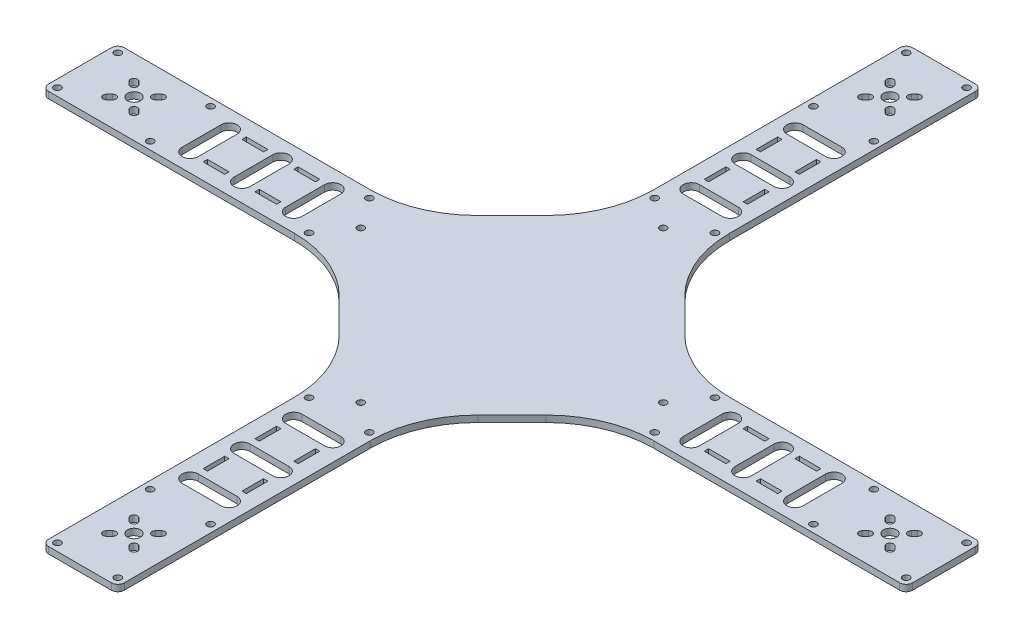
SolidWorks part; units mm, degrees
ref_plane "前视基准面" through (0, 0, 0) normal (0, 0, 1) x (1, 0, 0)
ref_plane "上视基准面" through (0, 0, 0) normal (0, 1, 0) x (1, 0, 0)
ref_plane "右视基准面" through (0, 0, 0) normal (1, 0, 0) x (0, 0, -1)
other "Configuration Table"
sketch "基本底盘" plane through (0, 0, 0) normal (0, 1, 0) x (1, 0, 0)
  line L0 (0, 0) -> (0, -350) construction
  line L1 (4.9497, -4.9497) -> (6.364, -6.364) construction
  line L4 (6.0811, -3.8184) -> (7.4953, -5.2326)
  line L5 (3.8184, -6.0811) -> (5.2326, -7.4953)
  line L6 (-17.5, 25) -> (17.5, 25)
  line L9 (-4.9497, -4.9497) -> (-6.364, -6.364) construction
  line L10 (-3.8184, -6.0811) -> (-5.2326, -7.4953)
  line L11 (-6.0811, -3.8184) -> (-7.4953, -5.2326)
  line L12 (-17.5, 25) -> (-17.5, -25)
  line L15 (-4.9497, 4.9497) -> (-6.364, 6.364) construction
  line L16 (-6.0811, 3.8184) -> (-7.4953, 5.2326)
  line L17 (-3.8184, 6.0811) -> (-5.2326, 7.4953)
  line L18 (17.5, 25) -> (17.5, -25)
  line L21 (4.9497, 4.9497) -> (6.364, 6.364) construction
  line L22 (3.8184, 6.0811) -> (5.2326, 7.4953)
  line L23 (6.0811, 3.8184) -> (7.4953, 5.2326)
  line L24 (0, -25) -> (0, -35)
  line L25 (-9, -35) -> (9, -35) construction
  line L26 (-9, -59) -> (9, -59) construction
  line L27 (-17.5, -25) -> (17.5, -25) construction
  line L28 (-17.5, 25) -> (17.5, -25) construction
  line L29 (17.5, 25) -> (-17.5, -25) construction
  line L30 (-17.5, 25) -> (-13.9645, 21.4645)
  line L31 (-17.5, 0) -> (17.5, 0) construction
  line L32 (-80, -175) -> (80, -175)
  line L33 (0, -95) -> (0, -255)
  line L34 (-32.1447, -127.1447) -> (-47.8553, -142.8553)
  line L35 (32.1447, -222.8553) -> (47.8553, -207.1447)
  line L36 (47.8553, -142.8553) -> (32.1447, -127.1447)
  line L37 (-47.8553, -207.1447) -> (-32.1447, -222.8553)
  line L38 (-13.9645, -21.4645) -> (-13.9645, -95) construction
  line L39 (-17.5, -25) -> (-17.5, -91.7893)
  line L40 (17.5, -25) -> (17.5, -91.7893)
  line L41 (0, -95) -> (0, -105)
  line L42 (-9, -31.25) -> (9, -31.25)
  line L43 (-9, -38.75) -> (9, -38.75)
  line L44 (-9, -55.25) -> (9, -55.25)
  line L45 (-9, -62.75) -> (9, -62.75)
  line L46 (-9, -83) -> (9, -83) construction
  line L47 (-9, -79.25) -> (9, -79.25)
  line L48 (-9, -86.75) -> (9, -86.75)
  line L49 (9, -38.75) -> (9, -55.25)
  line L50 (8, -42) -> (10, -42)
  line L51 (8, -42) -> (8, -52)
  line L52 (10, -42) -> (10, -52)
  line L53 (8, -52) -> (10, -52)
  line L54 (8, -42) -> (10, -52) construction
  line L55 (10, -42) -> (8, -52) construction
  line L56 (8, -66) -> (10, -76) construction
  line L57 (10, -66) -> (8, -76) construction
  line L58 (8, -66) -> (10, -66)
  line L59 (8, -66) -> (8, -76)
  line L60 (8, -76) -> (10, -76)
  line L61 (10, -66) -> (10, -76)
  line L62 (-8, -66) -> (-8, -76)
  line L63 (-8, -76) -> (-10, -76)
  line L64 (-10, -66) -> (-10, -76)
  line L65 (-8, -66) -> (-10, -66)
  line L66 (-8, -52) -> (-10, -52)
  line L67 (-8, -42) -> (-8, -52)
  line L68 (-8, -42) -> (-10, -42)
  line L69 (-10, -42) -> (-10, -52)
  line L70 (200, -157.5) -> (200, -192.5)
  line L71 (200, -157.5) -> (150, -157.5)
  line L72 (200, -192.5) -> (150, -192.5)
  line L73 (150, -175) -> (140, -175)
  line L74 (200, -157.5) -> (196.4645, -161.0355)
  line L75 (136.25, -184) -> (119.75, -184)
  line L76 (133, -183) -> (133, -185)
  line L77 (133, -183) -> (123, -183)
  line L78 (133, -185) -> (123, -185)
  line L79 (123, -183) -> (123, -185)
  line L80 (109, -183) -> (109, -185)
  line L81 (109, -183) -> (99, -183)
  line L82 (99, -183) -> (99, -185)
  line L83 (109, -185) -> (99, -185)
  line L84 (109, -167) -> (99, -167)
  line L85 (99, -167) -> (99, -165)
  line L86 (109, -165) -> (99, -165)
  line L87 (109, -167) -> (109, -165)
  line L88 (123, -167) -> (123, -165)
  line L89 (133, -167) -> (123, -167)
  line L90 (133, -167) -> (133, -165)
  line L91 (133, -165) -> (123, -165)
  line L92 (150, -157.5) -> (150, -192.5) construction
  line L93 (200, -157.5) -> (150, -192.5) construction
  line L94 (200, -192.5) -> (150, -157.5) construction
  line L95 (175, -157.5) -> (175, -192.5) construction
  line L96 (153.5355, -161.0355) -> (80, -161.0355) construction
  line L97 (133, -183) -> (123, -185) construction
  line L98 (133, -185) -> (123, -183) construction
  line L99 (109, -183) -> (99, -185) construction
  line L100 (109, -185) -> (99, -183) construction
  line L101 (150, -157.5) -> (83.2107, -157.5)
  line L102 (150, -192.5) -> (83.2107, -192.5)
  line L103 (170.0503, -179.9497) -> (168.636, -181.364) construction
  line L104 (171.1816, -181.0811) -> (169.7674, -182.4953)
  line L105 (168.9189, -178.8184) -> (167.5047, -180.2326)
  line L106 (170.0503, -170.0503) -> (168.636, -168.636) construction
  line L107 (168.9189, -171.1816) -> (167.5047, -169.7674)
  line L108 (171.1816, -168.9189) -> (169.7674, -167.5047)
  line L109 (179.9497, -170.0503) -> (181.364, -168.636) construction
  line L110 (178.8184, -168.9189) -> (180.2326, -167.5047)
  line L111 (181.0811, -171.1816) -> (182.4953, -169.7674)
  line L112 (179.9497, -179.9497) -> (181.364, -181.364) construction
  line L113 (181.0811, -178.8184) -> (182.4953, -180.2326)
  line L114 (178.8184, -181.0811) -> (180.2326, -182.4953)
  line L115 (140, -166) -> (140, -184) construction
  line L116 (143.75, -166) -> (143.75, -184)
  line L117 (136.25, -166) -> (136.25, -184)
  line L118 (116, -166) -> (116, -184) construction
  line L119 (119.75, -166) -> (119.75, -184)
  line L120 (112.25, -166) -> (112.25, -184)
  line L121 (92, -166) -> (92, -184) construction
  line L122 (95.75, -166) -> (95.75, -184)
  line L123 (88.25, -166) -> (88.25, -184)
  line L124 (17.5, -375) -> (-17.5, -375)
  line L125 (17.5, -375) -> (17.5, -325)
  line L126 (-17.5, -375) -> (-17.5, -325)
  line L127 (0, -325) -> (0, -315)
  line L128 (17.5, -375) -> (13.9645, -371.4645)
  line L129 (-9, -311.25) -> (-9, -294.75)
  line L130 (-8, -308) -> (-10, -308)
  line L131 (-8, -308) -> (-8, -298)
  line L132 (-10, -308) -> (-10, -298)
  line L133 (-8, -298) -> (-10, -298)
  line L134 (-8, -284) -> (-10, -284)
  line L135 (-8, -284) -> (-8, -274)
  line L136 (-8, -274) -> (-10, -274)
  line L137 (-10, -284) -> (-10, -274)
  line L138 (8, -284) -> (8, -274)
  line L139 (8, -274) -> (10, -274)
  line L140 (10, -284) -> (10, -274)
  line L141 (8, -284) -> (10, -284)
  line L142 (8, -298) -> (10, -298)
  line L143 (8, -308) -> (8, -298)
  line L144 (8, -308) -> (10, -308)
  line L145 (10, -308) -> (10, -298)
  line L146 (17.5, -325) -> (-17.5, -325) construction
  line L147 (17.5, -375) -> (-17.5, -325) construction
  line L148 (-17.5, -375) -> (17.5, -325) construction
  line L149 (17.5, -350) -> (-17.5, -350) construction
  line L150 (13.9645, -328.5355) -> (13.9645, -255) construction
  line L151 (-8, -308) -> (-10, -298) construction
  line L152 (-10, -308) -> (-8, -298) construction
  line L153 (-8, -284) -> (-10, -274) construction
  line L154 (-10, -284) -> (-8, -274) construction
  line L155 (17.5, -325) -> (17.5, -258.2107)
  line L156 (-17.5, -325) -> (-17.5, -258.2107)
  line L157 (-4.9497, -345.0503) -> (-6.364, -343.636) construction
  line L158 (-6.0811, -346.1816) -> (-7.4953, -344.7674)
  line L159 (-3.8184, -343.9189) -> (-5.2326, -342.5047)
  line L160 (4.9497, -345.0503) -> (6.364, -343.636) construction
  line L161 (3.8184, -343.9189) -> (5.2326, -342.5047)
  line L162 (6.0811, -346.1816) -> (7.4953, -344.7674)
  line L163 (4.9497, -354.9497) -> (6.364, -356.364) construction
  line L164 (6.0811, -353.8184) -> (7.4953, -355.2326)
  line L165 (3.8184, -356.0811) -> (5.2326, -357.4953)
  line L166 (-4.9497, -354.9497) -> (-6.364, -356.364) construction
  line L167 (-3.8184, -356.0811) -> (-5.2326, -357.4953)
  line L168 (-6.0811, -353.8184) -> (-7.4953, -355.2326)
  line L169 (9, -315) -> (-9, -315) construction
  line L170 (9, -318.75) -> (-9, -318.75)
  line L171 (9, -311.25) -> (-9, -311.25)
  line L172 (9, -291) -> (-9, -291) construction
  line L173 (9, -294.75) -> (-9, -294.75)
  line L174 (9, -287.25) -> (-9, -287.25)
  line L175 (9, -267) -> (-9, -267) construction
  line L176 (9, -270.75) -> (-9, -270.75)
  line L177 (9, -263.25) -> (-9, -263.25)
  line L178 (-200, -192.5) -> (-200, -157.5)
  line L179 (-200, -192.5) -> (-150, -192.5)
  line L180 (-200, -157.5) -> (-150, -157.5)
  line L181 (-150, -175) -> (-140, -175)
  line L182 (-200, -192.5) -> (-196.4645, -188.9645)
  line L183 (-136.25, -166) -> (-119.75, -166)
  line L184 (-133, -167) -> (-133, -165)
  line L185 (-133, -167) -> (-123, -167)
  line L186 (-133, -165) -> (-123, -165)
  line L187 (-123, -167) -> (-123, -165)
  line L188 (-109, -167) -> (-109, -165)
  line L189 (-109, -167) -> (-99, -167)
  line L190 (-99, -167) -> (-99, -165)
  line L191 (-109, -165) -> (-99, -165)
  line L192 (-109, -183) -> (-99, -183)
  line L193 (-99, -183) -> (-99, -185)
  line L194 (-109, -185) -> (-99, -185)
  line L195 (-109, -183) -> (-109, -185)
  line L196 (-123, -183) -> (-123, -185)
  line L197 (-133, -183) -> (-123, -183)
  line L198 (-133, -183) -> (-133, -185)
  line L199 (-133, -185) -> (-123, -185)
  line L200 (-150, -192.5) -> (-150, -157.5) construction
  line L201 (-200, -192.5) -> (-150, -157.5) construction
  line L202 (-200, -157.5) -> (-150, -192.5) construction
  line L203 (-175, -192.5) -> (-175, -157.5) construction
  line L204 (-153.5355, -188.9645) -> (-80, -188.9645) construction
  line L205 (-133, -167) -> (-123, -165) construction
  line L206 (-133, -165) -> (-123, -167) construction
  line L207 (-109, -167) -> (-99, -165) construction
  line L208 (-109, -165) -> (-99, -167) construction
  line L209 (-150, -192.5) -> (-83.2107, -192.5)
  line L210 (-150, -157.5) -> (-83.2107, -157.5)
  line L211 (-170.0503, -170.0503) -> (-168.636, -168.636) construction
  line L212 (-171.1816, -168.9189) -> (-169.7674, -167.5047)
  line L213 (-168.9189, -171.1816) -> (-167.5047, -169.7674)
  line L214 (-170.0503, -179.9497) -> (-168.636, -181.364) construction
  line L215 (-168.9189, -178.8184) -> (-167.5047, -180.2326)
  line L216 (-171.1816, -181.0811) -> (-169.7674, -182.4953)
  line L217 (-179.9497, -179.9497) -> (-181.364, -181.364) construction
  line L218 (-178.8184, -181.0811) -> (-180.2326, -182.4953)
  line L219 (-181.0811, -178.8184) -> (-182.4953, -180.2326)
  line L220 (-179.9497, -170.0503) -> (-181.364, -168.636) construction
  line L221 (-181.0811, -171.1816) -> (-182.4953, -169.7674)
  line L222 (-178.8184, -168.9189) -> (-180.2326, -167.5047)
  line L223 (-140, -184) -> (-140, -166) construction
  line L224 (-143.75, -184) -> (-143.75, -166)
  line L225 (-136.25, -184) -> (-136.25, -166)
  line L226 (-116, -184) -> (-116, -166) construction
  line L227 (-119.75, -184) -> (-119.75, -166)
  line L228 (-112.25, -184) -> (-112.25, -166)
  line L229 (-92, -184) -> (-92, -166) construction
  line L230 (-95.75, -184) -> (-95.75, -166)
  line L231 (-88.25, -184) -> (-88.25, -166)
  line L232 (0, -95) -> (-32.1447, -127.1447)
  line L233 (0, -95) -> (32.1447, -127.1447)
  line L234 (47.8553, -142.8553) -> (80, -175)
  line L235 (47.8553, -207.1447) -> (80, -175)
  line L236 (-80, -175) -> (-47.8553, -207.1447)
  line L237 (-80, -175) -> (-47.8553, -142.8553)
  line L238 (-32.1447, -222.8553) -> (0, -255)
  line L239 (0, -255) -> (32.1447, -222.8553)
  circle A0 centre (0, 0) radius 8 construction
  arc A3 (6.0811, -3.8184) -> (3.8184, -6.0811) centre (4.9497, -4.9497) ccw
  arc A4 (5.2326, -7.4953) -> (7.4953, -5.2326) centre (6.364, -6.364) ccw
  arc A7 (-3.8184, -6.0811) -> (-6.0811, -3.8184) centre (-4.9497, -4.9497) ccw
  arc A8 (-7.4953, -5.2326) -> (-5.2326, -7.4953) centre (-6.364, -6.364) ccw
  arc A11 (-6.0811, 3.8184) -> (-3.8184, 6.0811) centre (-4.9497, 4.9497) ccw
  arc A12 (-5.2326, 7.4953) -> (-7.4953, 5.2326) centre (-6.364, 6.364) ccw
  arc A15 (3.8184, 6.0811) -> (6.0811, 3.8184) centre (4.9497, 4.9497) ccw
  arc A16 (7.4953, 5.2326) -> (5.2326, 7.4953) centre (6.364, 6.364) ccw
  circle A17 centre (0, 0) radius 14 construction
  arc A18 (-9, -31.25) -> (-9, -38.75) centre (-9, -35) ccw
  arc A19 (9, -38.75) -> (9, -31.25) centre (9, -35) ccw
  circle A20 centre (0, 0) radius 3
  circle A21 centre (0, 0) radius 88.9 construction
  circle A22 centre (0, 0) radius 64.77 construction
  circle A23 centre (-13.9645, 21.4645) radius 1.6
  circle A24 centre (13.9645, 21.4645) radius 1.6
  circle A25 centre (13.9645, -21.4645) radius 1.6
  circle A26 centre (-13.9645, -21.4645) radius 1.6
  circle A27 centre (-13.9645, -95) radius 1.6
  circle A28 centre (13.9645, -95) radius 1.6
  circle A29 centre (0, -105) radius 1.6
  arc A30 (-9, -55.25) -> (-9, -62.75) centre (-9, -59) ccw
  arc A31 (9, -62.75) -> (9, -55.25) centre (9, -59) ccw
  arc A32 (-9, -79.25) -> (-9, -86.75) centre (-9, -83) ccw
  arc A33 (9, -86.75) -> (9, -79.25) centre (9, -83) ccw
  circle A34 centre (175, -175) radius 3
  circle A35 centre (196.4645, -161.0355) radius 1.6
  circle A36 centre (196.4645, -188.9645) radius 1.6
  circle A37 centre (153.5355, -188.9645) radius 1.6
  circle A38 centre (153.5355, -161.0355) radius 1.6
  circle A39 centre (80, -161.0355) radius 1.6
  circle A40 centre (80, -188.9645) radius 1.6
  circle A41 centre (175, -175) radius 8 construction
  circle A42 centre (175, -175) radius 14 construction
  circle A43 centre (175, -175) radius 88.9 construction
  circle A44 centre (175, -175) radius 64.77 construction
  circle A45 centre (70, -175) radius 1.6
  arc A46 (171.1816, -181.0811) -> (168.9189, -178.8184) centre (170.0503, -179.9497) ccw
  arc A47 (167.5047, -180.2326) -> (169.7674, -182.4953) centre (168.636, -181.364) ccw
  arc A48 (168.9189, -171.1816) -> (171.1816, -168.9189) centre (170.0503, -170.0503) ccw
  arc A49 (169.7674, -167.5047) -> (167.5047, -169.7674) centre (168.636, -168.636) ccw
  arc A50 (178.8184, -168.9189) -> (181.0811, -171.1816) centre (179.9497, -170.0503) ccw
  arc A51 (182.4953, -169.7674) -> (180.2326, -167.5047) centre (181.364, -168.636) ccw
  arc A52 (181.0811, -178.8184) -> (178.8184, -181.0811) centre (179.9497, -179.9497) ccw
  arc A53 (180.2326, -182.4953) -> (182.4953, -180.2326) centre (181.364, -181.364) ccw
  arc A54 (143.75, -166) -> (136.25, -166) centre (140, -166) ccw
  arc A55 (136.25, -184) -> (143.75, -184) centre (140, -184) ccw
  arc A56 (119.75, -166) -> (112.25, -166) centre (116, -166) ccw
  arc A57 (112.25, -184) -> (119.75, -184) centre (116, -184) ccw
  arc A58 (95.75, -166) -> (88.25, -166) centre (92, -166) ccw
  arc A59 (88.25, -184) -> (95.75, -184) centre (92, -184) ccw
  circle A60 centre (0, -350) radius 3
  circle A61 centre (13.9645, -371.4645) radius 1.6
  circle A62 centre (-13.9645, -371.4645) radius 1.6
  circle A63 centre (-13.9645, -328.5355) radius 1.6
  circle A64 centre (13.9645, -328.5355) radius 1.6
  circle A65 centre (13.9645, -255) radius 1.6
  circle A66 centre (-13.9645, -255) radius 1.6
  circle A67 centre (0, -350) radius 8 construction
  circle A68 centre (0, -350) radius 14 construction
  circle A69 centre (0, -350) radius 88.9 construction
  circle A70 centre (0, -350) radius 64.77 construction
  circle A71 centre (0, -245) radius 1.6
  arc A72 (-6.0811, -346.1816) -> (-3.8184, -343.9189) centre (-4.9497, -345.0503) ccw
  arc A73 (-5.2326, -342.5047) -> (-7.4953, -344.7674) centre (-6.364, -343.636) ccw
  arc A74 (3.8184, -343.9189) -> (6.0811, -346.1816) centre (4.9497, -345.0503) ccw
  arc A75 (7.4953, -344.7674) -> (5.2326, -342.5047) centre (6.364, -343.636) ccw
  arc A76 (6.0811, -353.8184) -> (3.8184, -356.0811) centre (4.9497, -354.9497) ccw
  arc A77 (5.2326, -357.4953) -> (7.4953, -355.2326) centre (6.364, -356.364) ccw
  arc A78 (-3.8184, -356.0811) -> (-6.0811, -353.8184) centre (-4.9497, -354.9497) ccw
  arc A79 (-7.4953, -355.2326) -> (-5.2326, -357.4953) centre (-6.364, -356.364) ccw
  arc A80 (9, -318.75) -> (9, -311.25) centre (9, -315) ccw
  arc A81 (-9, -311.25) -> (-9, -318.75) centre (-9, -315) ccw
  arc A82 (9, -294.75) -> (9, -287.25) centre (9, -291) ccw
  arc A83 (-9, -287.25) -> (-9, -294.75) centre (-9, -291) ccw
  arc A84 (9, -270.75) -> (9, -263.25) centre (9, -267) ccw
  arc A85 (-9, -263.25) -> (-9, -270.75) centre (-9, -267) ccw
  circle A86 centre (-175, -175) radius 3
  circle A87 centre (-196.4645, -188.9645) radius 1.6
  circle A88 centre (-196.4645, -161.0355) radius 1.6
  circle A89 centre (-153.5355, -161.0355) radius 1.6
  circle A90 centre (-153.5355, -188.9645) radius 1.6
  circle A91 centre (-80, -188.9645) radius 1.6
  circle A92 centre (-80, -161.0355) radius 1.6
  circle A93 centre (-175, -175) radius 8 construction
  circle A94 centre (-175, -175) radius 14 construction
  circle A95 centre (-175, -175) radius 88.9 construction
  circle A96 centre (-175, -175) radius 64.77 construction
  circle A97 centre (-70, -175) radius 1.6
  arc A98 (-171.1816, -168.9189) -> (-168.9189, -171.1816) centre (-170.0503, -170.0503) ccw
  arc A99 (-167.5047, -169.7674) -> (-169.7674, -167.5047) centre (-168.636, -168.636) ccw
  arc A100 (-168.9189, -178.8184) -> (-171.1816, -181.0811) centre (-170.0503, -179.9497) ccw
  arc A101 (-169.7674, -182.4953) -> (-167.5047, -180.2326) centre (-168.636, -181.364) ccw
  arc A102 (-178.8184, -181.0811) -> (-181.0811, -178.8184) centre (-179.9497, -179.9497) ccw
  arc A103 (-182.4953, -180.2326) -> (-180.2326, -182.4953) centre (-181.364, -181.364) ccw
  arc A104 (-181.0811, -171.1816) -> (-178.8184, -168.9189) centre (-179.9497, -170.0503) ccw
  arc A105 (-180.2326, -167.5047) -> (-182.4953, -169.7674) centre (-181.364, -168.636) ccw
  arc A106 (-143.75, -184) -> (-136.25, -184) centre (-140, -184) ccw
  arc A107 (-136.25, -166) -> (-143.75, -166) centre (-140, -166) ccw
  arc A108 (-119.75, -184) -> (-112.25, -184) centre (-116, -184) ccw
  arc A109 (-112.25, -166) -> (-119.75, -166) centre (-116, -166) ccw
  arc A110 (-95.75, -184) -> (-88.25, -184) centre (-92, -184) ccw
  arc A111 (-88.25, -166) -> (-95.75, -166) centre (-92, -166) ccw
  arc A112 (17.5, -258.2107) -> (32.1447, -222.8553) centre (67.5, -258.2107) cw
  arc A113 (-17.5, -258.2107) -> (-32.1447, -222.8553) centre (-67.5, -258.2107) ccw
  arc A114 (47.8553, -142.8553) -> (83.2107, -157.5) centre (83.2107, -107.5) ccw
  arc A115 (83.2107, -192.5) -> (47.8553, -207.1447) centre (83.2107, -242.5) ccw
  arc A116 (-47.8553, -207.1447) -> (-83.2107, -192.5) centre (-83.2107, -242.5) ccw
  arc A117 (-47.8553, -142.8553) -> (-83.2107, -157.5) centre (-83.2107, -107.5) cw
  arc A118 (32.1447, -127.1447) -> (17.5, -91.7893) centre (67.5, -91.7893) cw
  arc A119 (-32.1447, -127.1447) -> (-17.5, -91.7893) centre (-67.5, -91.7893) ccw
  point P14 (5.6569, -5.6569)
  point P28 (-5.6569, -5.6569)
  point P34 (0, 0)
  point P42 (-5.6569, 5.6569)
  point P48 (0, -175)
  point P53 (0, -175)
  point P56 (5.6569, 5.6569)
  point P61 (0, 0)
  point P63 (0, 8)
  point P73 (0, -35)
  point P80 (0, -59)
  point P87 (0, -83)
  point P93 (9, -47)
  point P95 (9, -71)
  point P125 (169.3431, -180.6569)
  point P139 (169.3431, -169.3431)
  point P145 (175, -175)
  point P152 (180.6569, -169.3431)
  point P161 (180.6569, -180.6569)
  point P166 (175, -175)
  point P177 (140, -175)
  point P184 (116, -175)
  point P191 (92, -175)
  point P197 (128, -184)
  point P199 (104, -184)
  point P226 (-5.6569, -344.3431)
  point P240 (5.6569, -344.3431)
  point P246 (0, -350)
  point P253 (5.6569, -355.6569)
  point P262 (-5.6569, -355.6569)
  point P267 (0, -350)
  point P278 (0, -315)
  point P285 (0, -291)
  point P292 (0, -267)
  point P298 (-9, -303)
  point P300 (-9, -279)
  point P327 (-169.3431, -169.3431)
  point P341 (-169.3431, -180.6569)
  point P347 (-175, -175)
  point P354 (-180.6569, -180.6569)
  point P363 (-180.6569, -169.3431)
  point P368 (-175, -175)
  point P379 (-140, -175)
  point P386 (-116, -175)
  point P393 (-92, -175)
  point P399 (-128, -166)
  point P401 (-104, -166)
  point P416 (0, -175)
  dimension "D1" = 16
  dimension "D3" = 28
  dimension "D2" = 6
  dimension "D4" = 350
  dimension "D5" = 129.54
  dimension "D9" = 3.2
  dimension "D11" = 3.2
  dimension "D12" = 10
  dimension "D13" = 3.2
  dimension "D14" = 10
  dimension "D15" = 3
  dimension "D20" = 50
  dimension "D6" = 35
  dimension "D7" = 50
  dimension "D8" = 5
  dimension "D10" = 2
  dimension "D16" = 2
  dimension "D17" = 10
  dimension "D18" = 2
  dimension "D19" = 4
extrude "凸台-拉伸1" add sketch "基本底盘" along normal blind 3
fillet "圆角3" radius 3 8 edges at (200, 1.5, 157.5) (200, 1.5, 192.5) (17.5, 1.5, 375) (-17.5, 1.5, 375) (-200, 1.5, 192.5) (-200, 1.5, 157.5) (-17.5, 1.5, -25) (17.5, 1.5, -25)
